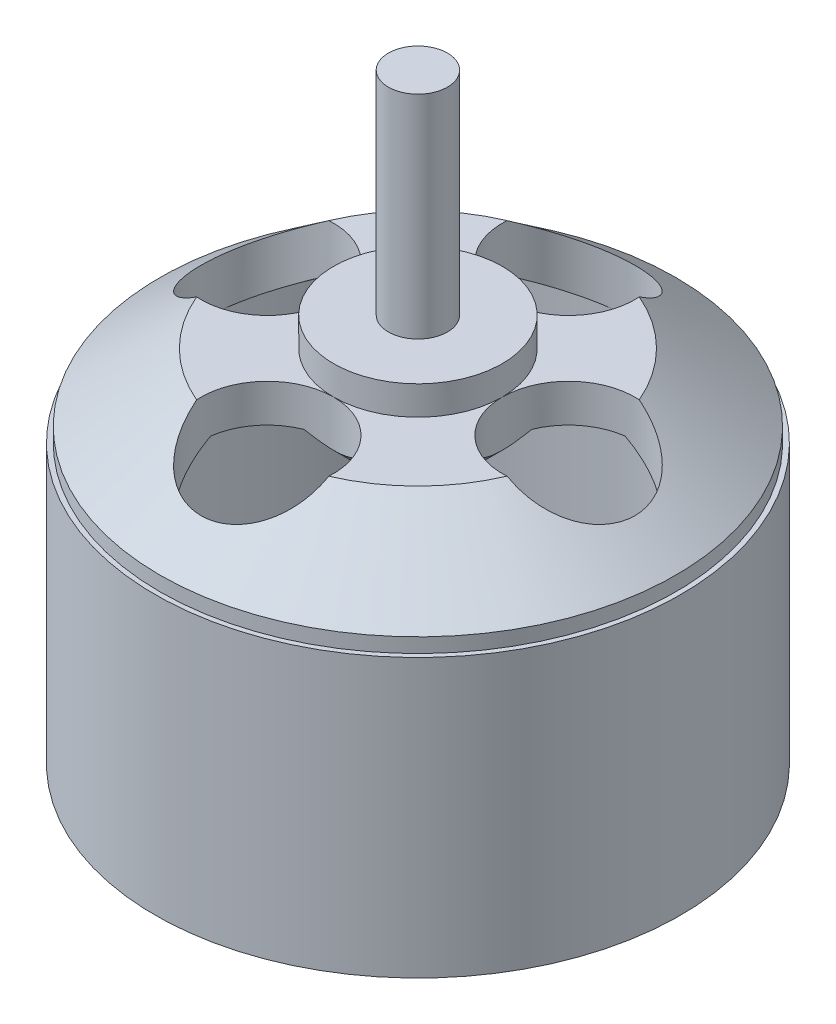
SolidWorks part; units mm, degrees
material "Plain Carbon Steel"
ref_plane "Front" through (0, 0, 0) normal (0, 0, 1) x (1, 0, 0)
ref_plane "Top" through (0, 0, 0) normal (0, 1, 0) x (1, 0, 0)
ref_plane "Right" through (0, 0, 0) normal (1, 0, 0) x (0, 0, -1)
sketch "Sketch1" plane through (0, 0, 0) normal (0, 0, 1) x (1, 0, 0)
  line L0 (0, 11.176) -> (1.5558, 11.176)
  line L1 (0, -50) -> (0, 50) construction
  line L2 (1.5558, 11.176) -> (1.5558, 0)
  line L3 (50, 0) -> (-50, 0) construction
  line L4 (1.5558, 0) -> (4.445, 0)
  line L5 (4.445, 0) -> (4.445, -1.524)
  line L6 (4.445, -1.524) -> (8.89, -1.524)
  line L7 (8.89, -1.524) -> (13.589, -5.08)
  line L8 (13.589, -5.08) -> (13.589, -5.842)
  line L9 (13.589, -5.842) -> (13.843, -5.842)
  line L10 (13.843, -5.842) -> (13.843, -20.4724)
  line L11 (13.589, -20.4724) -> (13.589, -23.0124)
  line L12 (13.589, -23.0124) -> (12.7, -26.67)
  line L13 (12.7, -26.67) -> (3.81, -26.67)
  line L14 (3.81, -26.67) -> (3.81, -26.924)
  line L15 (3.81, -26.924) -> (1.5558, -26.924)
  line L16 (1.5558, -26.924) -> (1.5558, -28.956)
  line L17 (1.5558, -28.956) -> (0, -28.956)
  line L18 (0, -28.956) -> (0, 11.176)
  line L19 (13.589, -20.4724) -> (13.843, -20.4724)
  dimension "D1" = 13.843
  dimension "D2" = 1.5557
  dimension "D3" = 11.176
  dimension "D4" = 4.445
  dimension "D5" = 1.524
  dimension "D6" = 8.89
  dimension "D7" = 4.318
  dimension "D8" = 0.762
  dimension "D9" = 0.254
  dimension "D10" = 14.6304
  dimension "D11" = 2.54
  dimension "D12" = 25.146
  dimension "D13" = 12.7
  dimension "D14" = 3.81
  dimension "D15" = 0.254
  dimension "D16" = 40.132
revolve "Revolve1" add sketch "Sketch1" angle 360 about L18
sketch "Sketch3" plane through (0, -20.4724, 0) normal (0, -1, 0) x (1, 0, 0)
  circle A0 centre (0, 0) radius 1.5558 construction
  circle A1 centre (0, 0) radius 13.843 construction
  circle A2 centre (0, 0) radius 1.5558
  circle A3 centre (0, 0) radius 13.843
extrude "Cut-Extrude2" cut sketch "Sketch3" along normal through all
sketch "Sketch5" plane through (0, 0, 0) normal (0, 0, 1) x (1, 0, 0)
  line L0 (11.343, -5.8885) -> (11.343, -24.7656)
  line L1 (11.343, -24.7656) -> (1.5558, -24.7656)
  line L2 (1.5558, -24.7656) -> (1.5558, -5.842)
  line L3 (1.5558, -5.842) -> (2.5558, -5.842)
  line L4 (2.5558, -5.842) -> (4.8737, -3.524)
  line L5 (4.8737, -3.524) -> (8.2185, -3.524)
  line L6 (8.2185, -3.524) -> (11.343, -5.8885)
  line L18 (13.589, -23.0124) -> (13.589, -20.4724)
  line L19 (12.7, -26.67) -> (13.589, -23.0124)
  line L20 (3.81, -26.67) -> (12.7, -26.67)
  line L21 (3.81, -26.924) -> (3.81, -26.67)
  line L22 (1.5558, -26.924) -> (3.81, -26.924)
  line L23 (1.5558, -28.956) -> (1.5558, -26.924)
  line L24 (0, -28.956) -> (1.5558, -28.956)
  line L25 (0, 11.176) -> (0, -28.956)
  line L26 (1.5558, 11.176) -> (0, 11.176)
  line L27 (1.5558, 0) -> (1.5558, 11.176)
  line L28 (4.445, 0) -> (1.5558, 0)
  line L29 (4.445, -1.524) -> (4.445, 0)
  line L30 (8.89, -1.524) -> (4.445, -1.524)
  line L31 (13.589, -5.08) -> (8.89, -1.524)
  line L32 (13.589, -5.842) -> (13.589, -5.08)
  line L33 (13.843, -5.842) -> (13.589, -5.842)
  line L34 (13.843, -20.4724) -> (13.843, -5.842)
  line L35 (13.589, -20.4724) -> (13.843, -20.4724)
  line L36 (13.589, -23.0124) -> (13.589, -20.4724) construction
  line L37 (12.7, -26.67) -> (13.589, -23.0124) construction
  line L38 (3.81, -26.67) -> (12.7, -26.67) construction
  line L39 (3.81, -26.924) -> (3.81, -26.67) construction
  line L40 (1.5558, -26.924) -> (3.81, -26.924) construction
  line L41 (1.5558, -28.956) -> (1.5558, -26.924) construction
  line L42 (0, -28.956) -> (1.5558, -28.956) construction
  line L43 (0, 11.176) -> (0, -28.956) construction
  line L44 (1.5558, 11.176) -> (0, 11.176) construction
  line L45 (1.5558, 0) -> (1.5558, 11.176) construction
  line L46 (4.445, 0) -> (1.5558, 0) construction
  line L47 (4.445, -1.524) -> (4.445, 0) construction
  line L48 (8.89, -1.524) -> (4.445, -1.524) construction
  line L49 (13.589, -5.08) -> (8.89, -1.524) construction
  line L50 (13.589, -5.842) -> (13.589, -5.08) construction
  line L51 (13.843, -5.842) -> (13.589, -5.842) construction
  line L52 (13.843, -20.4724) -> (13.843, -5.842) construction
  line L53 (13.589, -20.4724) -> (13.843, -20.4724) construction
  point P10 (11.343, -24.7656)
  dimension "D2" = 2.5
  dimension "D3" = 2
  dimension "D4" = 2
  dimension "D5" = 1
  dimension "D6" = 45
  dimension "D1" = 0
revolve "Cut-Revolve1" cut sketch "Sketch5" angle 360 about L43
sketch "Sketch2" plane through (0, -1.524, 0) normal (0, 1, 0) x (1, 0, 0)
  circle A0 centre (0, 7.9375) radius 3.4925
  circle A1 centre (7.9375, 0) radius 3.4925
  circle A2 centre (0, -7.9375) radius 3.4925
  circle A3 centre (-7.9375, 0) radius 3.4925
  circle A5 centre (0, 0) radius 4.445 construction
  circle A7 centre (0, 0) radius 4.445 construction
  dimension "D2" = 6.985
extrude "Cut-Extrude1" cut sketch "Sketch2" against normal blind 5.08
